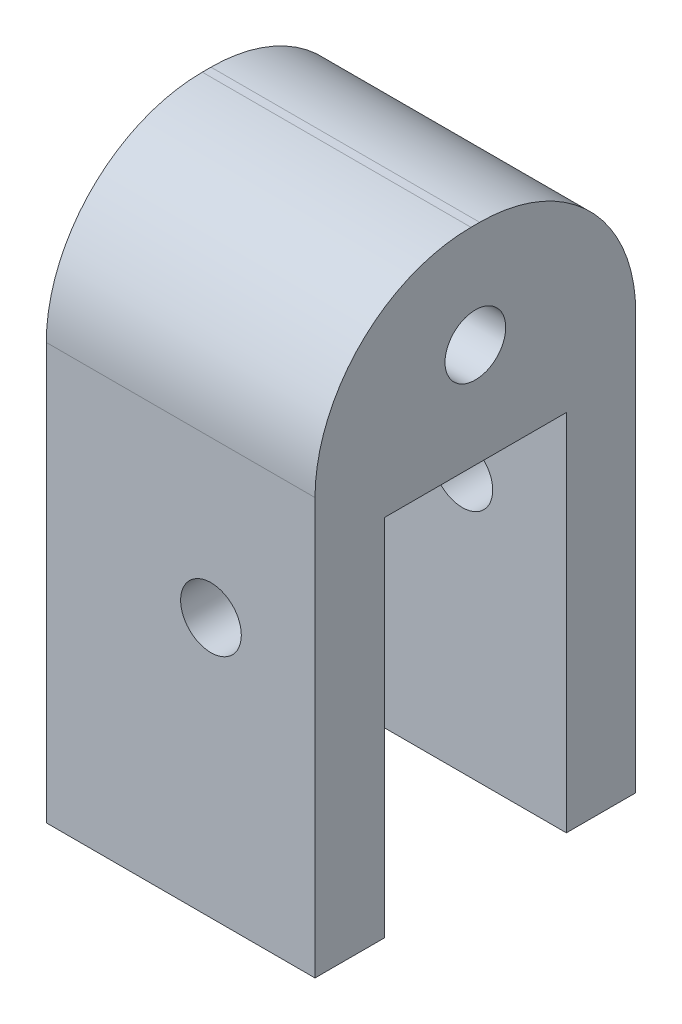
SolidWorks part; units mm, degrees
ref_plane "正面" through (0, 0, 0) normal (0, 0, 1) x (1, 0, 0)
ref_plane "平面" through (0, 0, 0) normal (0, 1, 0) x (1, 0, 0)
ref_plane "右側面" through (0, 0, 0) normal (1, 0, 0) x (0, 0, -1)
sketch "ｽｹｯﾁ1" plane through (0, 0, 0) normal (0, 1, 0) x (1, 0, 0)
  line L0 (0, 18.5) -> (0, 0)
  line L1 (0, -10.175) -> (0, 10.175) construction
  line L2 (0, 0) -> (15.5, 0)
  line L3 (-8.525, 0) -> (8.525, 0) construction
  line L4 (15.5, 0) -> (15.5, 4)
  line L5 (15.5, 4) -> (4, 4)
  line L6 (4, 4) -> (4, 14.5)
  line L7 (4, 14.5) -> (15.5, 14.5)
  line L8 (15.5, 14.5) -> (15.5, 18.5)
  line L9 (15.5, 18.5) -> (0, 18.5)
  dimension "D1" = 4
  dimension "D2" = 4
  dimension "D3" = 10.5
  dimension "D4" = 11.5
  dimension "D5" = 11.5
  dimension "D6" = 4
extrude "ﾎﾞｽ - 押し出し1" add sketch "ｽｹｯﾁ1" along normal blind 21
sketch "ｽｹｯﾁ2" plane through (0, 0, 0) normal (0, 0, 1) x (1, 0, 0)
  line L0 (15.5, 21) -> (15.5, 33)
  line L1 (15.5, 33) -> (0, 33)
  line L2 (0, -10.175) -> (0, 10.175) construction
  line L3 (0, 33) -> (0, 21)
  line L4 (0, 21) -> (15.5, 21) construction
  line L5 (0, 21) -> (15.5, 21)
  dimension "D1" = 12
extrude "ﾎﾞｽ - 押し出し2" add sketch "ｽｹｯﾁ2" against normal blind 18.5
sketch "ｽｹｯﾁ3" plane through (0, 0, 0) normal (0, 0, 1) x (1, 0, 0)
  line L0 (15.5, 33) -> (15.5, 0) construction
  line L1 (15.5, 33) -> (0, 33) construction
  circle A0 centre (9.5, 27) radius 4.25
  dimension "D1" = 8.5
  dimension "D2" = 6
  dimension "D3" = 6
sketch "ｽｹｯﾁ4" plane through (0, 0, 0) normal (0, 0, 1) x (1, 0, 0)
  line L0 (9.5, 0) -> (9.5, 33) construction
  line L1 (8.525, 0) -> (-8.525, 0) construction
  line L2 (15.5, 33) -> (0, 33) construction
  line L3 (15.5, 33) -> (15.5, 0) construction
  circle A0 centre (9.5, 15) radius 1.75
  dimension "D2" = 3.5
  dimension "D3" = 15
  dimension "D1" = 6
extrude "ｶｯﾄ - 押し出し2" cut sketch "ｽｹｯﾁ4" against normal through all
sketch "ｽｹｯﾁ5" plane through (0, 0, 0) normal (-1, 0, 0) x (0, 0, 1)
  line L0 (-18.5, 33) -> (0, 33) construction
  line L1 (-18.5, 33) -> (-18.5, 0) construction
  circle A0 centre (-9.25, 27) radius 1.75
  dimension "D1" = 3.5
  dimension "D3" = 9.25
  dimension "D2" = 6
extrude "ｶｯﾄ - 押し出し3" cut sketch "ｽｹｯﾁ5" against normal through all
sketch "ｽｹｯﾁ6" plane through (4, 0, 0) normal (1, 0, 0) x (0, 0, -1)
  line L0 (8.525, 0) -> (-8.525, 0) construction
  line L1 (4, 21) -> (4, 0) construction
  circle A0 centre (9.25, 5) radius 1.75
  dimension "D1" = 5
  dimension "D2" = 3.5
  dimension "D3" = 5.25
extrude "ｶｯﾄ - 押し出し4" cut sketch "ｽｹｯﾁ6" against normal through all
fillet "ﾌｨﾚｯﾄ1" radius 9 2 edges at (7.75, 33, 0) (7.75, 33, -18.5)
